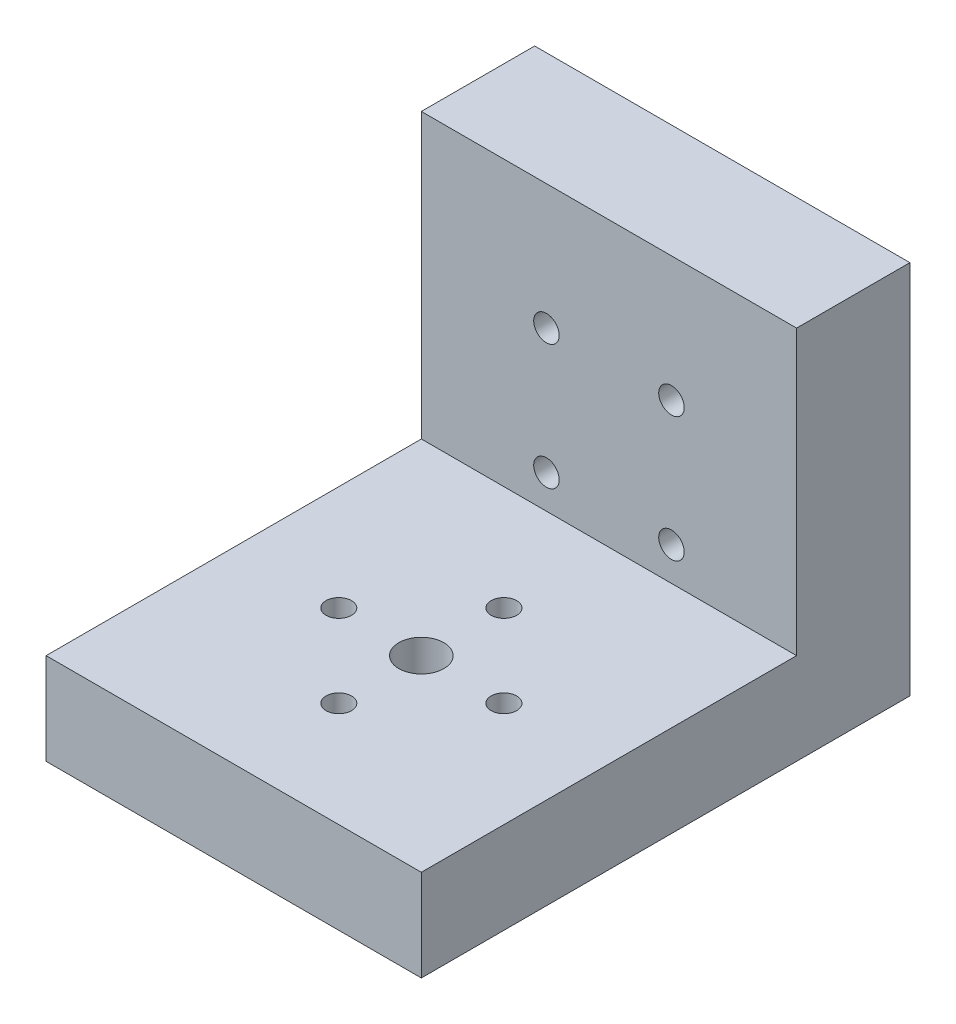
SolidWorks part; units mm, degrees
ref_plane "Front Plane" through (0, 0, 0) normal (1, 0, 0) x (0, 1, 0)
ref_plane "Top Plane" through (0, 0, 0) normal (0, 0, 1) x (0, 1, 0)
ref_plane "Right Plane" through (0, 0, 0) normal (0, 1, 0) x (-1, 0, 0)
sketch "Sketch2" plane through (0, 0, 0) normal (0, 0, 1) x (0, 1, 0)
  line L1 (0, 0) -> (50, 0)
  line L2 (0, 0) -> (0, -50)
  line L3 (0, -50) -> (50, -50)
  line L4 (50, 0) -> (50, -50)
  dimension "D1" = 50
  dimension "D2" = 50
extrude "Boss-Extrude1" add sketch "Sketch2" along normal blind 15.1
sketch "Sketch3" plane through (0, 0, 15.1) normal (0, 0, 1) x (1, 0, 0)
  line L0 (16.67, 54.4208) -> (16.67, -8.0872) construction
  line L1 (33.33, 54.4208) -> (33.33, -9.1603) construction
  line L2 (-5.4491, 33.33) -> (58.579, 33.33) construction
  line L3 (-5.4491, 16.67) -> (59.205, 16.67) construction
  line L4 (0, 0) -> (50, 0) construction
  line L6 (50, 0) -> (50, 50) construction
  circle A0 centre (16.67, 33.33) radius 1.7
  circle A1 centre (33.33, 33.33) radius 1.7
  circle A2 centre (16.67, 16.67) radius 1.7
  circle A3 centre (33.33, 16.67) radius 1.7
  dimension "D5" = 3.4
  dimension "D1" = 16.67
  dimension "D2" = 33.33
  dimension "D3" = 16.67
  dimension "D4" = 33.33
extrude "Cut-Extrude1" cut sketch "Sketch3" against normal through all
sketch "Sketch4" plane through (0, 0, 15.1) normal (0, 0, 1) x (1, 0, 0)
  line L0 (50, 0) -> (50, 50) construction
  line L1 (0, 0) -> (50, 0)
  line L2 (0, 0) -> (0, 12.2)
  line L3 (0, 12.2) -> (50, 12.2)
  line L4 (50, 0) -> (50, 12.2)
  dimension "D1" = 12.2
extrude "Boss-Extrude2" add sketch "Sketch4" along normal blind 50
sketch "Sketch5" plane through (0, 12.2, 0) normal (0, 1, 0) x (-1, 0, 0)
  line L0 (-25, 65.1) -> (-25, 15.1) construction
  line L1 (-50, 40.1) -> (0, 40.1) construction
  line L2 (-50, 65.1) -> (-50, 15.1) construction
  line L3 (0, 65.1) -> (0, 15.1) construction
  line L4 (-50, 65.1) -> (0, 65.1) construction
  line L5 (-50, 15.1) -> (0, 15.1) construction
  circle A0 centre (-25, 40.1) radius 3
  circle A1 centre (-25, 40.1) radius 11 construction
  circle A2 centre (-36, 40.1) radius 1.7
  circle A3 centre (-25, 51.1) radius 1.7
  circle A4 centre (-14, 40.1) radius 1.7
  circle A5 centre (-25, 29.1) radius 1.7
  dimension "D1" = 6
  dimension "D2" = 22
  dimension "D3" = 3.4
extrude "Cut-Extrude2" cut sketch "Sketch5" against normal through all
equation "\"P\"= 300'N"
equation "\"E\"= 3030'PETG modulus, MPa=N/mm^2"
equation "\"Sy\"= 51.4'PETG yield strength, MPa"
equation "\"SF\"= 3'Safety factor"
equation "\"dmax\"= 0.30'Max deflection, mm"
equation "\"b\"= 50'Plate width, mm"
equation "\"L1\"= 50'Feature 1 design length, mm"
equation "\"e1\"= 18'Shaft offset, mm"
equation "\"M1\"= \"P\" * \"e1\"'Feature 1 moment, N·mm"
equation "\"h1stress\"= ( ( 6 * \"M1\" * \"SF\" ) / ( \"b\" * \"Sy\" ) ) ^ 0.5'Feature 1 thickness from stress, mm"
equation "\"h1def\"= ( ( 6 * \"M1\" * \"L1\" ^ 2 ) / ( \"E\" * \"b\" * \"dmax\" ) ) ^ ( 1 / 3 )'Feature 1 thickness from deflection, mm"
equation "\"h1\"= 12.2'Final Feature 1 thickness, mm"
equation "\"L2\"= 50'Feature 2 design length, mm"
equation "\"holeA\"= 16.67'First wall-mount hole center, mm"
equation "\"holeB\"= 33.33'Second wall-mount hole center, mm"
equation "\"e2\"= \"L2\" - \"holeB\" + \"e1\"'Feature 2 moment arm, mm"
equation "\"M2\"= \"P\" * \"e2\"'Feature 2 moment, N·mm"
equation "\"h2stress\"= ( ( 6 * \"M2\" * \"SF\" ) / ( \"b\" * \"Sy\" ) ) ^ 0.5'Feature 2 thickness from stress, mm"
equation "\"h2def\"= ( ( 6 * \"M2\" * \"L2\" ^ 2 ) / ( \"E\" * \"b\" * \"dmax\" ) ) ^ ( 1 / 3 )'Feature 2 thickness from deflection, mm"
equation "\"h2\"= 15.1'Final Feature 2 thickness, mm"
equation "\"holeDia\" = 3.4"
equation "\"shaftDia\"= 6'Motor shaft diameter"
equation "\"motorPCD\"= 22'4-M3 bolt-circle diameter"
